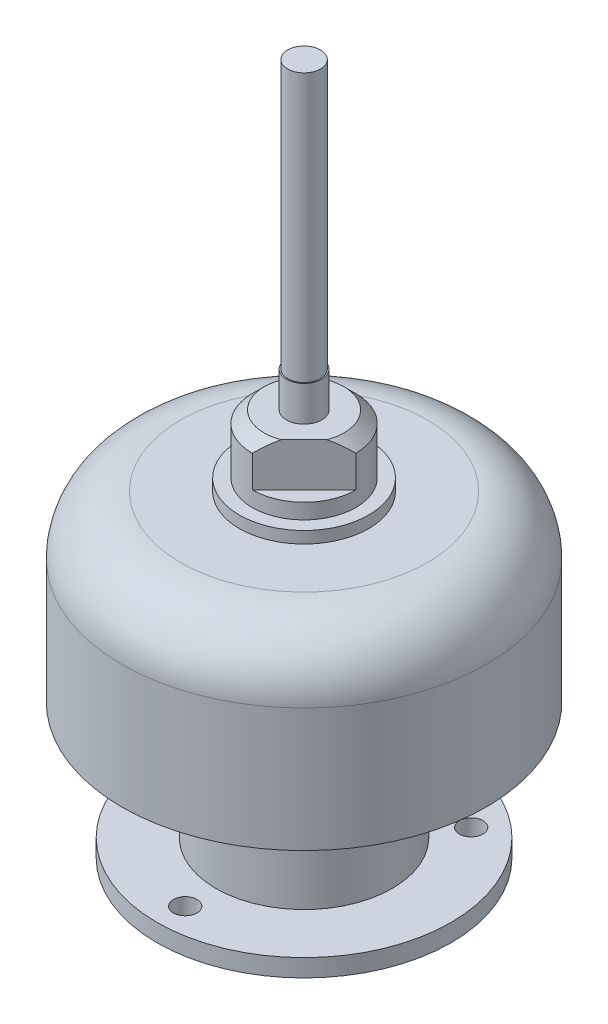
SolidWorks part; units mm, degrees
ref_plane "Front Plane" through (0, 0, 0) normal (0, 0, 1) x (1, 0, 0)
ref_plane "Top Plane" through (0, 0, 0) normal (0, 1, 0) x (1, 0, 0)
ref_plane "Right Plane" through (0, 0, 0) normal (1, 0, 0) x (0, 0, -1)
sketch "Sketch1" plane through (0, 0, 0) normal (0, 1, 0) x (1, 0, 0)
  circle A0 centre (0, 0) radius 12.5
  dimension "D1" = 25
extrude "Extrude1" add sketch "Sketch1" along normal blind 1.5
sketch "Sketch2" plane through (0, 1.5, 0) normal (0, 1, 0) x (1, 0, 0)
  circle A0 centre (0, 0) radius 7.5
  dimension "D1" = 15
extrude "Extrude2" add sketch "Sketch2" along normal blind 5
sketch "Sketch3" plane through (0, 6.5, 0) normal (0, 1, 0) x (1, 0, 0)
  circle A0 centre (0, 0) radius 5
  dimension "D1" = 10
extrude "Extrude3" add sketch "Sketch3" along normal blind 5
sketch "Sketch4" plane through (0, 11.5, 0) normal (0, 1, 0) x (1, 0, 0)
  circle A0 centre (0, 0) radius 15.5
  dimension "D1" = 31
extrude "Extrude4" add sketch "Sketch4" along normal blind 15.5
sketch "Sketch5" plane through (0, 27, 0) normal (0, 1, 0) x (1, 0, 0)
  circle A0 centre (0, 0) radius 5.5
  dimension "D1" = 11
extrude "Extrude5" add sketch "Sketch5" along normal blind 1
sketch "Sketch6" plane through (0, 28, 0) normal (0, 1, 0) x (1, 0, 0)
  circle A0 centre (0, 0) radius 4.4
  dimension "D1" = 8.8
extrude "Extrude6" add sketch "Sketch6" along normal blind 5
sketch "Sketch7" plane through (0, 33, 0) normal (0, 1, 0) x (1, 0, 0)
  line L0 (0, 4.4) -> (-4.4, 0)
  line L1 (4.4, 0) -> (0, -4.4)
  circle A0 centre (0, 0) radius 4.4 construction
  arc A1 (-4.4, 0) -> (0, 4.4) centre (0, 0) cw
  arc A2 (4.4, 0) -> (0, -4.4) centre (0, 0) cw
extrude "Extrude7" cut sketch "Sketch7" against normal blind 3.7
sketch "Sketch8" plane through (0, 33, 0) normal (0, 1, 0) x (1, 0, 0)
  circle A0 centre (0, 0) radius 1.5
  dimension "D1" = 3
extrude "Extrude8" add sketch "Sketch8" along normal blind 3
sketch "Sketch9" plane through (0, 36, 0) normal (0, 1, 0) x (1, 0, 0)
  circle A0 centre (0, 0) radius 1.4
  dimension "D1" = 2.8
extrude "Extrude9" add sketch "Sketch9" along normal blind 22.8
sketch "Sketch10" plane through (0, 0, 0) normal (0, -1, 0) x (1, 0, 0)
  circle A0 centre (0, 0) radius 4.4
  dimension "D1" = 8.8
extrude "Extrude10" cut sketch "Sketch10" against normal blind 2
sketch "Sketch11" plane through (0, 2, 0) normal (0, -1, 0) x (1, 0, 0)
  circle A0 centre (0, 0) radius 1.5
  dimension "D1" = 3
extrude "Extrude11" add sketch "Sketch11" along normal blind 3.3
sketch "Sketch12" plane through (0, 0, 0) normal (0, -1, 0) x (1, 0, 0)
  circle A0 centre (0, 0) radius 10.1028
  circle A1 centre (0, 10.1028) radius 1
  circle A2 centre (-6.35, -7.8577) radius 1
  circle A3 centre (6.35, -7.8577) radius 1
  dimension "D1" = 2
  dimension "D2" = 2
  dimension "D3" = 2
  dimension "D4" = 19.05
  dimension "D5" = 19.05
  dimension "D6" = 12.7
extrude "Extrude12" cut sketch "Sketch12" against normal up to next contours A1 | A3 | A2
fillet "Fillet1" radius 5 1 edges at (0, 27, 15.5)
chamfer "Chamfer1" distance 1 angle 45 2 edges at (3.1113, 33, -3.1113) (-3.1113, 33, 3.1113)
equation "\"D5@Sketch12\" = \"D4@Sketch12\""
